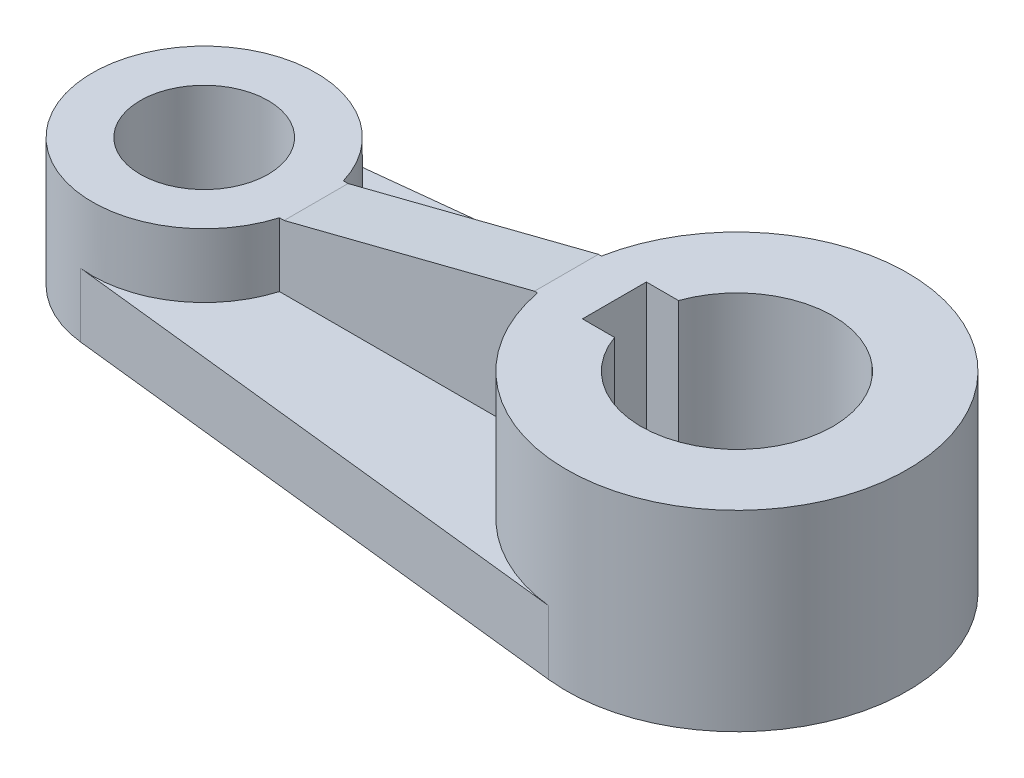
SolidWorks part; units mm, degrees
ref_plane "Front Plane" through (0, 0, 0) normal (0, 0, 1) x (1, 0, 0)
ref_plane "Top Plane" through (0, 0, 0) normal (0, 1, 0) x (1, 0, 0)
ref_plane "Right Plane" through (0, 0, 0) normal (1, 0, 0) x (0, 0, -1)
sketch "Sketch1" plane through (0, 0, 0) normal (0, 1, 0) x (1, 0, 0)
  circle A0 centre (0, 0) radius 32
  circle A1 centre (0, 0) radius 18
  dimension "D1" = 64
  dimension "D2" = 36
extrude "Boss-Extrude1" add sketch "Sketch1" along normal blind 36
sketch "Sketch2" plane through (0, 0, 0) normal (0, 1, 0) x (1, 0, 0)
  circle A0 centre (-100, 0) radius 21
  circle A1 centre (-100, 0) radius 12
  dimension "D1" = 42
  dimension "D2" = 24
  dimension "D3" = 100
extrude "Boss-Extrude2" add sketch "Sketch2" along normal blind 24 separate body
sketch "Sketch3" plane through (0, 0, 0) normal (0, -1, 0) x (1, 0, 0)
  line L0 (-102.31, 20.8726) -> (-3.52, 31.8058)
  line L1 (19.8, 0) -> (-19.8, 0) construction
  line L2 (-102.31, -20.8726) -> (-3.52, -31.8058)
  circle A0 centre (0, 0) radius 32 construction
  circle A1 centre (-100, 0) radius 21 construction
  arc A2 (-3.52, -31.8058) -> (-3.52, 31.8058) centre (0, 0) ccw
  arc A3 (-102.31, 20.8726) -> (-102.31, -20.8726) centre (-100, 0) ccw
  circle A4 centre (0, 0) radius 18 construction
  circle A5 centre (-100, 0) radius 12 construction
  circle A6 centre (0, 0) radius 18
  circle A7 centre (-100, 0) radius 12
  point P8 (0, 33.2419)
  point P9 (0, 33.632)
extrude "Boss-Extrude3" add sketch "Sketch3" against normal blind 12
sketch "Sketch4" plane through (0, 36, 0) normal (0, 1, 0) x (1, 0, 0)
  line L0 (0, 0) -> (-44.0803, 0) construction
  line L1 (-23.0006, 6) -> (-16.9706, 6)
  line L2 (-23.0006, 6) -> (-23.0006, -6)
  line L3 (-23.0006, -6) -> (-16.9706, -6)
  circle A0 centre (0, 0) radius 18 construction
  arc A1 (-16.9706, 6) -> (-16.9706, -6) centre (0, 0) ccw
  dimension "D1" = 6.03
  dimension "D2" = 12
extrude "Cut-Extrude1" cut sketch "Sketch4" against normal through all
sketch "Sketch5" plane through (0, 0, 0) normal (0, 0, 1) x (1, 0, 0)
  line L0 (-80.173, 12) -> (-80.173, 24)
  line L1 (-3.52, 12) -> (-102.31, 12) construction
  line L2 (-79, 24) -> (-121, 24) construction
  line L4 (-32, 36) -> (-30.3337, 36)
  line L5 (32, 36) -> (-32, 36) construction
  line L6 (-30.3337, 36) -> (-30.3337, 12)
  line L7 (-30.3337, 12) -> (-80.173, 12)
  line L8 (-80.173, 24) -> (-79, 24)
  line L9 (-79, 24) -> (-32, 36)
  line L10 (-102.31, 12) -> (-102.31, 0) construction
  point P18 (0, 0)
  dimension "D1" = 22.137
  dimension "D2" = 30.3337
extrude "Boss-Extrude4" add sketch "Sketch5" along normal mid plane 12
